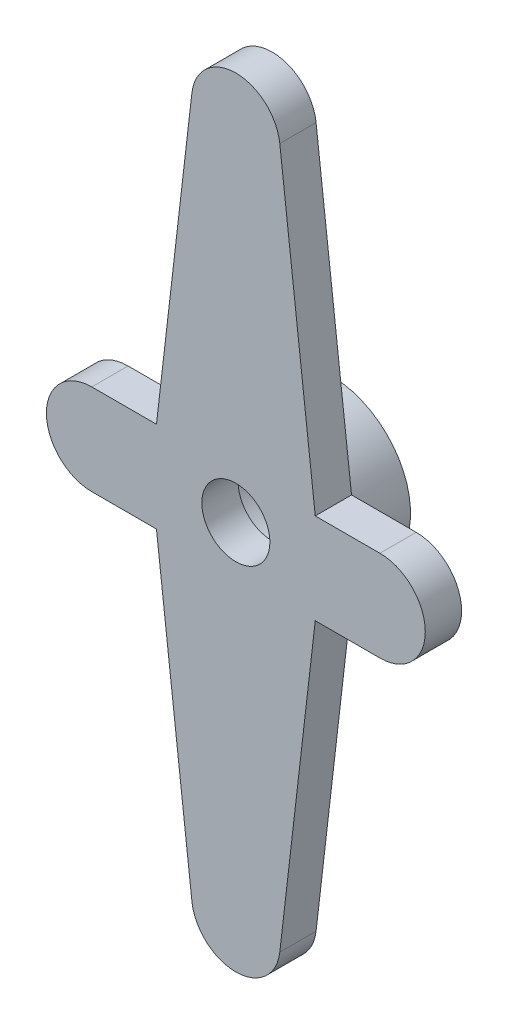
SolidWorks part; units mm, degrees
ref_plane "前视基准面" through (0, 0, 0) normal (0, 0, 1) x (1, 0, 0)
ref_plane "上视基准面" through (0, 0, 0) normal (0, 1, 0) x (1, 0, 0)
ref_plane "右视基准面" through (0, 0, 0) normal (1, 0, 0) x (0, 0, -1)
sketch "草图1" plane through (0, 0, 0) normal (0, 0, 1) x (1, 0, 0)
  line L0 (-14.1764, 5.0501) -> (14.5332, 5.0501) construction
  line L1 (66.0735, 5.0501) -> (-21.5084, 5.0501) construction
  line L2 (0, 22.21) -> (0, -8.5869) construction
  line L3 (-6.35, 5.0501) -> (7.5685, 5.0501) construction
  line L4 (-6.35, 7.0501) -> (-3.5, 7.0501)
  line L6 (-3.5, 7.0501) -> (-1.9369, 20.4853)
  line L7 (6.35, 7.0501) -> (3.5, 7.0501)
  line L8 (3.5, 7.0501) -> (1.9369, 20.4853)
  line L9 (-6.35, 3.0501) -> (-3.5, 3.0501)
  line L10 (-3.5, 3.0501) -> (-1.9369, -10.3851)
  line L11 (3.5, 3.0501) -> (1.9369, -10.3851)
  line L12 (6.35, 3.0501) -> (3.5, 3.0501)
  arc A0 (-6.35, 7.0501) -> (-6.35, 3.0501) centre (-6.35, 5.0501) ccw
  arc A2 (1.9369, 20.4853) -> (-1.9369, 20.4853) centre (0, 20.26) ccw
  arc A3 (6.35, 7.0501) -> (6.35, 3.0501) centre (6.35, 5.0501) cw
  arc A4 (1.9369, -10.3851) -> (-1.9369, -10.3851) centre (0, -10.1598) cw
  point P9 (-0.1725, 5.0501)
  dimension "D1" = 2
  dimension "D5" = 3.9
  dimension "D4" = 3.5
extrude "凸台-拉伸1" add sketch "草图1" along normal blind 1.6
sketch "草图2" plane through (0, 0, 0) normal (0, 0, -1) x (-1, 0, 0)
  circle A0 centre (0, 5.05) radius 2.5
  circle A1 centre (0, 5.05) radius 3.5
  dimension "D1" = 7
extrude "凸台-拉伸2" add sketch "草图2" along normal blind 2.6
sketch "草图5" plane through (0, 0, -2.6) normal (0, 0, -1) x (-1, 0, 0)
  line L0 (0, 5.05) -> (7, 5.05) construction
  line L1 (0, 5.05) -> (0, 12.05) construction
sketch "草图6" plane through (0, 0, 1.6) normal (0, 0, 1) x (1, 0, 0)
  line L0 (0, 18.0088) -> (0, -4.4714) construction
  line L1 (0, 5.05) -> (5.9251, 5.05) construction
sketch "草图7" plane through (0, 0, 0) normal (0, 0, -1) x (-1, 0, 0)
  circle A0 centre (0, 5.05) radius 1.5
  dimension "D1" = 3
extrude "切除-拉伸1" cut sketch "草图7" against normal blind 6
